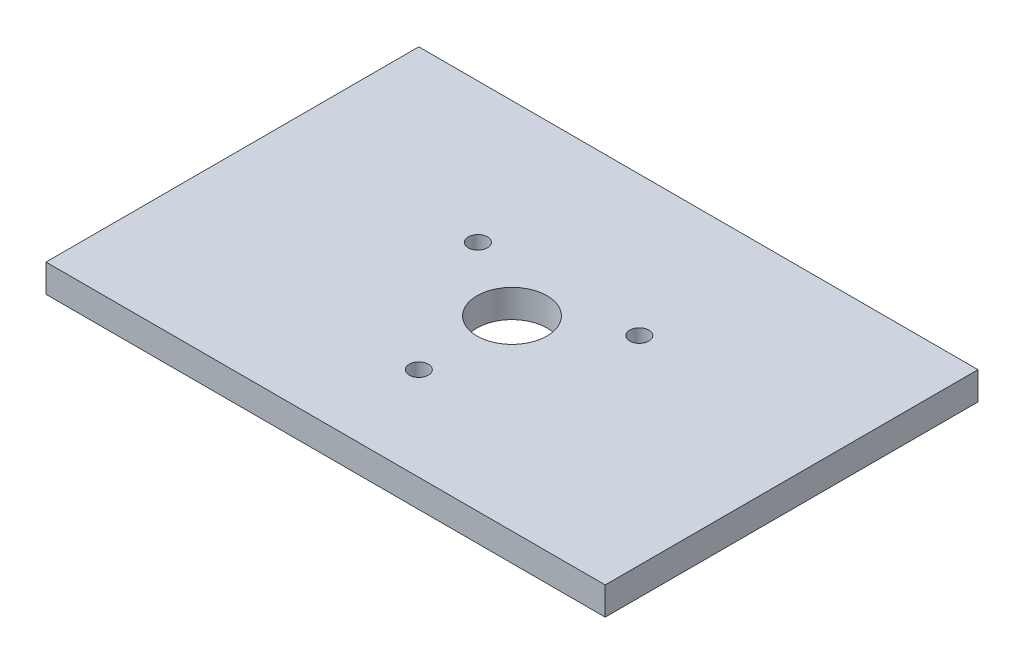
SolidWorks part; units mm, degrees
material "6061 合金"
ref_plane "前视基准面" through (0, 0, 0) normal (0, 0, 1) x (1, 0, 0)
ref_plane "上视基准面" through (0, 0, 0) normal (0, 1, 0) x (1, 0, 0)
ref_plane "右视基准面" through (0, 0, 0) normal (1, 0, 0) x (0, 0, -1)
sketch "草图1" plane through (0, 0, 0) normal (0, 1, 0) x (1, 0, 0)
  line L1 (-60, 40) -> (60, 40)
  line L2 (-60, 40) -> (-60, -40)
  line L3 (-60, -40) -> (60, -40)
  line L4 (60, 40) -> (60, -40)
  line L5 (-60, 40) -> (60, -40) construction
  line L6 (-60, -40) -> (60, 40) construction
  dimension "D2" = 120
  dimension "D3" = 80
extrude "凸台-拉伸1" add sketch "草图1" along normal blind 6
sketch "草图3" plane through (0, 6, 0) normal (0, 1, 0) x (1, 0, 0)
  circle A0 centre (0, 0) radius 20 construction
  circle A1 centre (0, -20) radius 2.05
  circle A2 centre (-17.3205, 10) radius 2.05
  circle A3 centre (17.3205, 10) radius 2.05
  point P12 (0, 0)
  dimension "D1" = 4.1
  dimension "D2" = 40
  dimension "D3" = 3
extrude "φ4.1孔1" cut sketch "草图3" against normal blind 5
sketch "草图4" plane through (0, 0, 0) normal (0, -1, 0) x (1, 0, 0)
  line L0 (0, 0) -> (0, -19)
  line L1 (0, 0) -> (-16.4545, 9.5)
  line L2 (0, 0) -> (16.4545, 9.5)
  circle A0 centre (-16.4545, 9.5) radius 2.05
  circle A1 centre (16.4545, 9.5) radius 2.05
  circle A2 centre (0, -19) radius 2.05
  point P8 (0, 0)
  point P14 (0, 0)
  dimension "D3" = 4.1
  dimension "D1" = 19
  dimension "D2" = 3
  dimension "D4" = 3
extrude "φ4.1孔2" cut sketch "草图4" against normal blind 5
sketch "草图5" plane through (0, 0, 0) normal (0, -1, 0) x (1, 0, 0)
  circle A0 centre (0, 0) radius 19 construction
  circle A1 centre (-16.4545, 9.5) radius 4
  circle A2 centre (16.4545, 9.5) radius 4
  circle A3 centre (0, -19) radius 4
  point P14 (0, 0)
  dimension "D1" = 8
  dimension "D2" = 3
extrude "切除-拉伸3" cut sketch "草图5" against normal blind 3
sketch "草图6" plane through (0, 0, 0) normal (0, -1, 0) x (1, 0, 0)
  circle A0 centre (0, 0) radius 7.5
  dimension "D1" = 15
extrude "切除-拉伸4" cut sketch "草图6" against normal blind 10
sketch "草图8" plane through (0, 6, 0) normal (0, 1, 0) x (1, 0, 0)
  circle A0 centre (0, 0) radius 12
